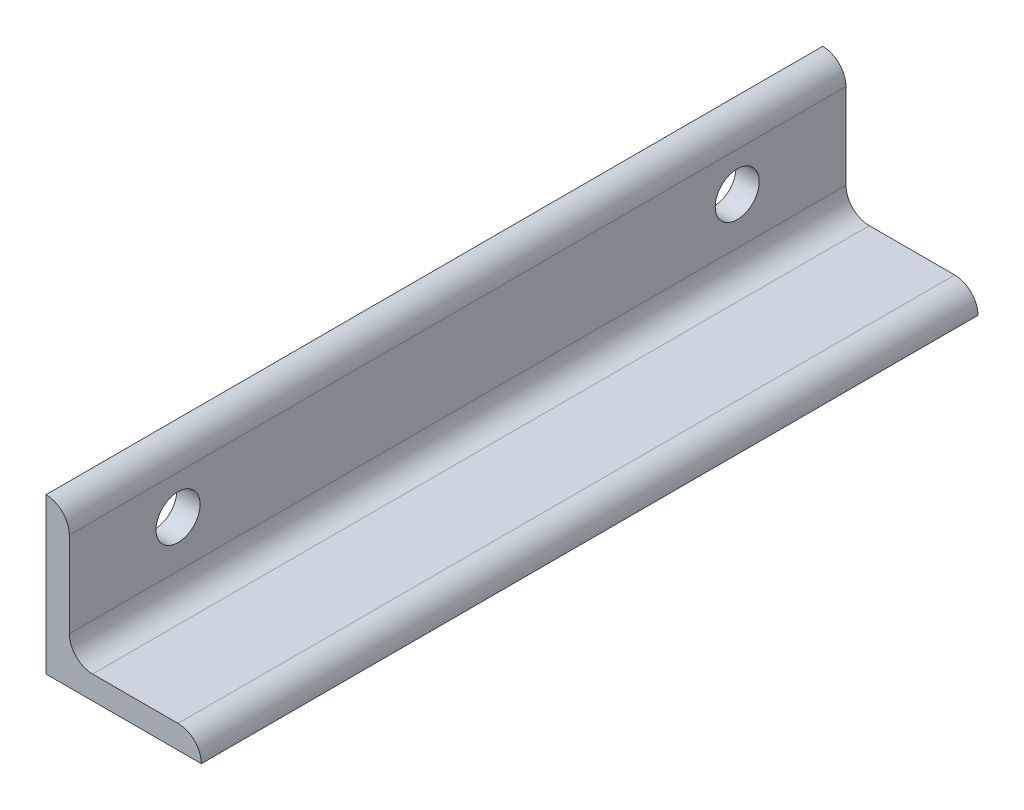
SolidWorks part; units mm, degrees
material "Low Carbon Steel"
ref_plane "Front Plane" through (0, 0, 0) normal (0, 0, 1) x (1, 0, 0)
ref_plane "Top Plane" through (0, 0, 0) normal (0, 1, 0) x (1, 0, 0)
ref_plane "Right Plane" through (0, 0, 0) normal (1, 0, 0) x (0, 0, -1)
sketch "Sketch1" plane through (0, 0, 0) normal (0, 0, 1) x (1, 0, 0)
  line L0 (0, 0) -> (0, 31.75)
  line L2 (0, 0) -> (31.75, 0)
  line L3 (26.9875, 4.7625) -> (9.525, 4.7625)
  line L4 (4.7625, 26.9875) -> (4.7625, 9.525)
  arc A0 (4.7625, 26.9875) -> (0, 31.75) centre (0, 26.9875) ccw
  arc A1 (4.7625, 9.525) -> (9.525, 4.7625) centre (9.525, 9.525) ccw
  arc A2 (26.9875, 4.7625) -> (31.75, 0) centre (26.9875, 0) cw
extrude "Boss-Extrude1" add sketch "Sketch1" along normal mid plane 158.75 contours L0 A0 L4 A1 L3 A2 L2
hole_wizard "M8 Clearance Hole1" positions "Sketch2" profile "Sketch3" hole size "M8" standard "Peddi DIN" end condition through all
sketch "Sketch2" plane through (0, 0, 0) normal (-1, 0, 0) x (0, 0, 1)
  line L0 (-57.15, 19.05) -> (57.15, 19.05) construction
  line L3 (0, 0) -> (0, 19.05) construction
  line L4 (79.375, 0) -> (-79.375, 0) construction
  point P0 (-57.15, 19.05)
  point P2 (57.15, 19.05)
  dimension "D1" = 114.3
  dimension "D2" = 19.05
sketch "Sketch3" plane through (0, 19.05, -57.15) normal (0, 1, 0) x (0, 0, 1)
  line L0 (0, 0) -> (0, 31.75)
  line L1 (0, 31.75) -> (4.5, 31.75)
  line L2 (4.5, 31.75) -> (4.5, 0)
  line L5 (4.5, 0) -> (0, 0)
  line L11 (0, -6.35) -> (0, 107.95) construction
  dimension "Thru Hole Dia." = 9
  dimension "Thru Hole Depth" = 31.75
other "Freeze***"
